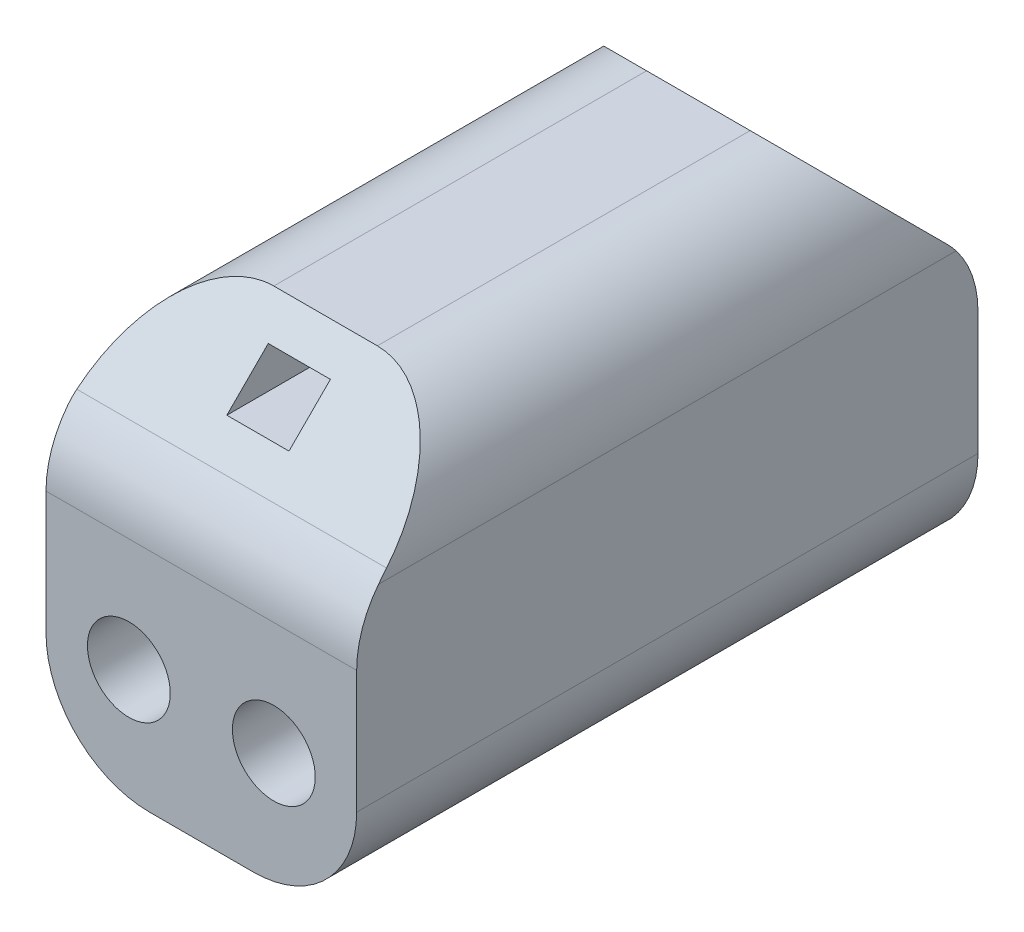
SolidWorks part; units mm, degrees
ref_plane "Front Plane" through (0, 0, 0) normal (0, 0, 1) x (1, 0, 0)
ref_plane "Top Plane" through (0, 0, 0) normal (0, 1, 0) x (1, 0, 0)
ref_plane "Right Plane" through (0, 0, 0) normal (1, 0, 0) x (0, 0, -1)
sketch "Sketch2" plane through (0, 0, 0) normal (1, 0, 0) x (0, 0, -1)
  line L0 (-7.9672, -29.2167) -> (-7.9672, -16.2167)
  line L1 (-7.9672, -16.2167) -> (-1.9672, -10.2167)
  line L2 (-1.9672, -10.2167) -> (16.0328, -10.2167)
  line L3 (16.0328, -10.2167) -> (22.0328, -16.2167)
  line L4 (22.0328, -16.2167) -> (22.0328, -29.2167)
  line L5 (22.0328, -29.2167) -> (-7.9672, -29.2167)
  dimension "D1" = 45
  dimension "D2" = 45
  dimension "D4" = 30
extrude "Boss-Extrude2" add sketch "Sketch2" along normal mid plane 15 separate body
fillet "Fillet2" radius 5 2 edges at (0, -16.2167, 7.9672) (0, -16.2167, -22.0328)
sketch "Sketch4" plane through (0, 0, 0) normal (0, 0, 1) x (1, 0, 0)
  line L3 (-1.5, -11.4845) -> (1.5, -11.4845)
  line L4 (-1.5, -11.4845) -> (-1.5, -13.4845)
  line L5 (-1.5, -13.4845) -> (1.5, -13.4845)
  line L6 (1.5, -11.4845) -> (1.5, -13.4845)
  line L7 (-1.5, -11.4845) -> (1.5, -13.4845) construction
  line L8 (-1.5, -13.4845) -> (1.5, -11.4845) construction
  line L10 (-7.5, -10.2167) -> (-7.5, -14.7523) construction
  line L11 (7.5, -10.2167) -> (7.5, -14.7523) construction
  line L12 (-7.5, -18.2878) -> (-7.5, -29.2167) construction
  line L13 (7.5, -18.2878) -> (7.5, -29.2167) construction
  line L14 (7.5, -10.2167) -> (-7.5, -10.2167) construction
  line L15 (7.5, -18.2878) -> (-7.5, -18.2878) construction
  line L16 (7.5, -29.2167) -> (-7.5, -29.2167) construction
  circle A0 centre (-3.5, -23.7523) radius 2
  circle A1 centre (3.5, -23.7523) radius 2
  point P11 (0, -12.4845)
  dimension "D1" = 4
  dimension "D2" = 4
  dimension "D3" = 4
  dimension "D4" = 4
  dimension "D10" = 5.4645
  dimension "D11" = 5.4645
  dimension "D5" = 3
  dimension "D6" = 2
  dimension "D7" = 6
  dimension "D8" = 6
  dimension "D9" = 1.2678
extrude "Cut-Extrude1" cut sketch "Sketch4" against normal mid plane 200
fillet "Fillet3" radius 5 2 edges at (7.5, -29.2167, -7.0328) (-7.5, -29.2167, -7.0328)
fillet "Fillet4" radius 5 2 edges at (7.5, -10.2167, -7.0328) (-7.5, -10.2167, -7.0328)
